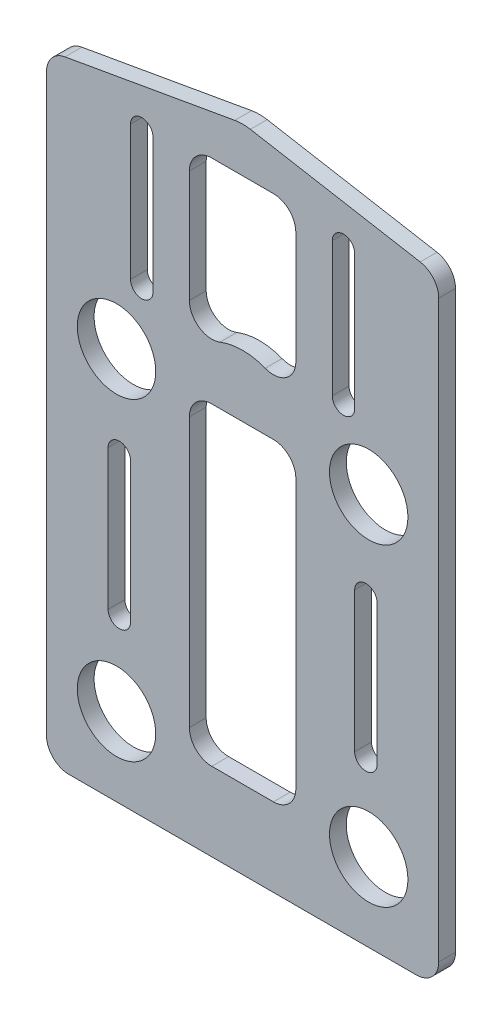
SolidWorks part; units mm, degrees
ref_plane "Front Plane" through (0, 0, 0) normal (0, 0, 1) x (1, 0, 0)
ref_plane "Top Plane" through (0, 0, 0) normal (0, 1, 0) x (1, 0, 0)
ref_plane "Right Plane" through (0, 0, 0) normal (1, 0, 0) x (0, 0, -1)
ref_plane "Plane1" through (0, 0, 0) normal (0, 0, -1) x (-1, 0, 0)
sketch "Sketch1" plane through (0, 0, 0) normal (0, 0, -1) x (-1, 0, 0)
  line L0 (-4.75, 14.512) -> (-4.75, 24.512)
  line L1 (-2.75, 26.512) -> (2.75, 26.512)
  line L2 (4.75, 24.512) -> (4.75, 14.512)
  line L3 (4.75, 5.512) -> (4.75, -18.488)
  line L4 (2.75, -20.488) -> (-2.75, -20.488)
  line L5 (-4.75, -18.488) -> (-4.75, 5.512)
  line L6 (-2.75, 7.512) -> (2.75, 7.512)
  line L7 (15.8473, 27.7794) -> (0.6946, 30.4512)
  line L8 (-0.6946, 30.4512) -> (-15.8473, 27.7794)
  line L9 (-17.5, 25.8098) -> (-17.5, -25.488)
  line L10 (-15.5, -27.488) -> (15.5, -27.488)
  line L11 (17.5, -25.488) -> (17.5, 25.8098)
  line L12 (12, -0.488) -> (12, -12.988)
  line L13 (10, -12.988) -> (10, -0.488)
  line L14 (10, 25.512) -> (10, 13.512)
  line L15 (8, 13.512) -> (8, 25.512)
  line L16 (-10, -0.488) -> (-10, -12.988)
  line L17 (-12, -12.988) -> (-12, -0.488)
  line L18 (-8, 25.512) -> (-8, 13.512)
  line L19 (-10, 13.512) -> (-10, 25.512)
  arc A0 (2.0177, 12.6509) -> (-2.0177, 12.6509) centre (0, 7.5228) ccw
  arc A1 (-2.0177, 12.6509) -> (-4.75, 14.512) centre (-2.75, 14.512) cw
  arc A2 (-4.75, 24.512) -> (-2.75, 26.512) centre (-2.75, 24.512) cw
  arc A3 (2.75, 26.512) -> (4.75, 24.512) centre (2.75, 24.512) cw
  arc A4 (4.75, 14.512) -> (2.0177, 12.6509) centre (2.75, 14.512) cw
  arc A5 (4.75, -18.488) -> (2.75, -20.488) centre (2.75, -18.488) cw
  arc A6 (-2.75, -20.488) -> (-4.75, -18.488) centre (-2.75, -18.488) cw
  arc A7 (-4.75, 5.512) -> (-2.75, 7.512) centre (-2.75, 5.512) cw
  arc A8 (2.75, 7.512) -> (4.75, 5.512) centre (2.75, 5.512) cw
  arc A9 (17.5, 25.8098) -> (15.8473, 27.7794) centre (15.5, 25.8098) ccw
  arc A10 (0.6946, 30.4512) -> (-0.6946, 30.4512) centre (0, 26.512) ccw
  arc A11 (-15.8473, 27.7794) -> (-17.5, 25.8098) centre (-15.5, 25.8098) ccw
  arc A12 (-17.5, -25.488) -> (-15.5, -27.488) centre (-15.5, -25.488) ccw
  arc A13 (15.5, -27.488) -> (17.5, -25.488) centre (15.5, -25.488) ccw
  circle A14 centre (11.25, 7.512) radius 3.5
  circle A15 centre (11.25, -20.488) radius 3.5
  circle A16 centre (-11.25, -20.488) radius 3.5
  circle A17 centre (-11.25, 7.512) radius 3.5
  arc A18 (10, -0.488) -> (12, -0.488) centre (11, -0.488) cw
  arc A19 (12, -12.988) -> (10, -12.988) centre (11, -12.988) cw
  arc A20 (8, 25.512) -> (10, 25.512) centre (9, 25.512) cw
  arc A21 (10, 13.512) -> (8, 13.512) centre (9, 13.512) cw
  arc A22 (-12, -0.488) -> (-10, -0.488) centre (-11, -0.488) cw
  arc A23 (-10, -12.988) -> (-12, -12.988) centre (-11, -12.988) cw
  arc A24 (-10, 25.512) -> (-8, 25.512) centre (-9, 25.512) cw
  arc A25 (-8, 13.512) -> (-10, 13.512) centre (-9, 13.512) cw
extrude "Boss-Extrude1" add sketch "Sketch1" against normal blind 1.5
